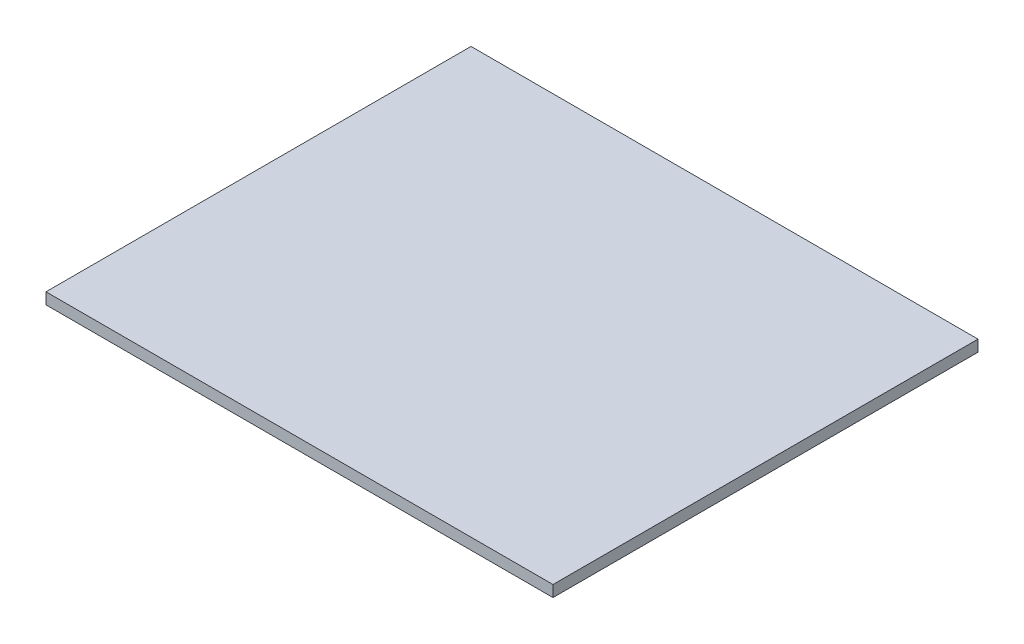
SolidWorks part; units mm, degrees
ref_plane "前视基准面" through (0, 0, 0) normal (0, 0, 1) x (1, 0, 0)
ref_plane "上视基准面" through (0, 0, 0) normal (0, 1, 0) x (1, 0, 0)
ref_plane "右视基准面" through (0, 0, 0) normal (1, 0, 0) x (0, 0, -1)
sketch "草图1" plane through (0, 0, 0) normal (0, 1, 0) x (1, 0, 0)
  line L1 (-178.9318, 150) -> (178.9318, 150)
  line L2 (-178.9318, 150) -> (-178.9318, -150)
  line L3 (-178.9318, -150) -> (178.9318, -150)
  line L4 (178.9318, 150) -> (178.9318, -150)
  line L5 (-178.9318, 150) -> (178.9318, -150) construction
  line L6 (-178.9318, -150) -> (178.9318, 150) construction
  point P0 (0, 0)
  dimension "D1" = 300
  dimension "D2" = 357.8635
extrude "凸台-拉伸1" add sketch "草图1" along normal blind 8
